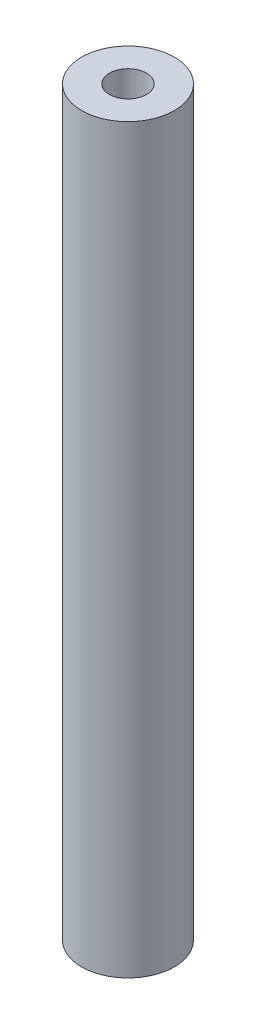
SolidWorks part; units mm, degrees
ref_plane "Front Plane" through (0, 0, 0) normal (0, 0, 1) x (1, 0, 0)
ref_plane "Top Plane" through (0, 0, 0) normal (0, 1, 0) x (1, 0, 0)
ref_plane "Right Plane" through (0, 0, 0) normal (1, 0, 0) x (0, 0, -1)
sketch "Sketch1" plane through (0, 0, 0) normal (0, 1, 0) x (1, 0, 0)
  line L0 (0, 0) -> (0, 180.5285) construction
  line L1 (0, 0) -> (61.9422, 0) construction
  circle A23 centre (0, 0) radius 1
  circle A24 centre (0, 0) radius 2.5
  dimension "D1" = 5
  dimension "D2" = 2
extrude "Boss-Extrude1" add sketch "Sketch1" along normal blind 40
equation "\"Base thickness\"= 3mm"
equation "\"Base attach hole diameter\"= 2mm"
equation "\"Base attach spacer diameter\"= 5mm"
equation "\"Base attach spacer height\"= 40mm"
equation "\"D1@Sketch1\"=\"Base attach spacer diameter\""
equation "\"D2@Sketch1\"=\"Base attach hole diameter\""
equation "\"D1@Boss-Extrude1\"=\"Base attach spacer height\""
